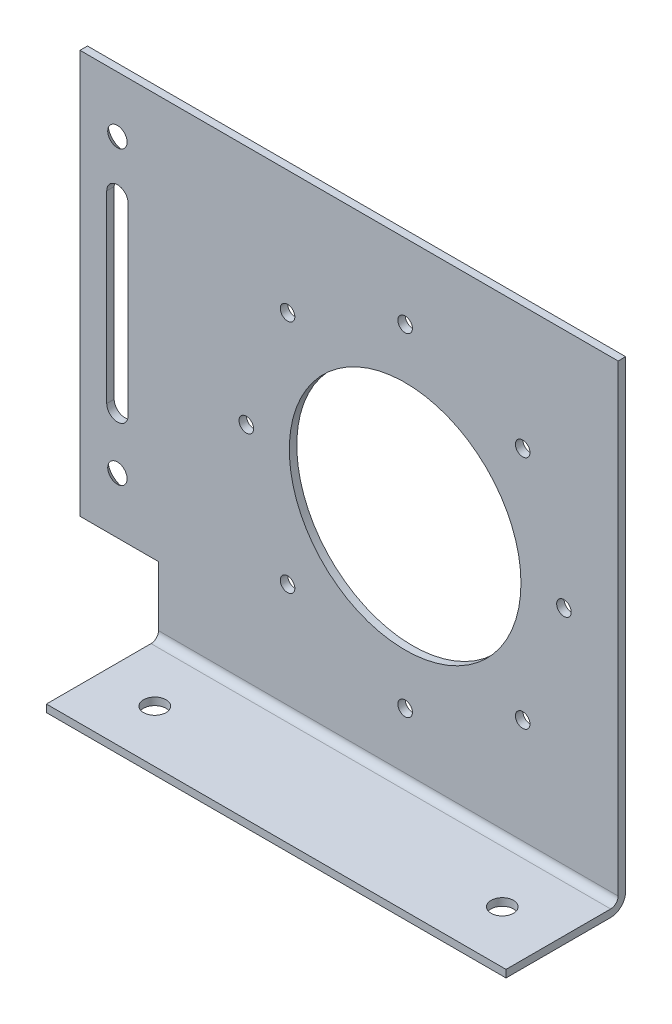
SolidWorks part; units mm, degrees
ref_plane "Ebene vorne" through (0, 0, 0) normal (0, 0, 1) x (1, 0, 0)
ref_plane "Ebene oben" through (0, 0, 0) normal (0, 1, 0) x (1, 0, 0)
ref_plane "Ebene rechts" through (0, 0, 0) normal (1, 0, 0) x (0, 0, -1)
sketch "Skizze1" plane through (0, 0, 0) normal (0, 0, 1) x (1, 0, 0)
  line L0 (-69.0234, -46.6458) -> (-48.0234, -46.6458)
  line L1 (74.9766, -66.6458) -> (-48.0234, -66.6458)
  line L2 (74.9766, -66.6458) -> (74.9766, 61.3542)
  line L3 (74.9766, 61.3542) -> (-69.0234, 61.3542)
  line L4 (-69.0234, -46.6458) -> (-69.0234, 61.3542)
  line L5 (74.9766, -66.6458) -> (-69.0234, 61.3542) construction
  line L6 (74.9766, 61.3542) -> (-48.0234, -39.2981) construction
  line L7 (-48.0234, -46.6458) -> (-48.0234, -66.6458)
  point P0 (0, 0)
  dimension "D1" = 128
  dimension "D2" = 144
  dimension "D3" = 21
  dimension "D4" = 20
extrude "Aufsatz-Linear austragen1" add sketch "Skizze1" along normal blind 2
sketch "Skizze2" plane through (0, 0, 0) normal (0, 0, -1) x (-1, 0, 0)
  line L1 (-74.9766, -66.6458) -> (48.0234, -66.6458)
  line L2 (-74.9766, -66.6458) -> (-74.9766, -64.6458)
  line L3 (-74.9766, -64.6458) -> (48.0234, -64.6458)
  line L5 (48.0234, -64.6458) -> (48.0234, -66.6458)
  line L6 (48.0234, -46.6458) -> (48.0234, -66.6458) construction
  dimension "D1" = 2
extrude "Aufsatz-Linear austragen2" add sketch "Skizze2" along normal blind 30
fillet "Verrundung1" radius 2 1 edges at (13.4766, -64.6458, 0)
fillet "Verrundung2" radius 4 1 edges at (13.4766, -66.6458, 2)
sketch "Skizze3" plane through (0, -66.6458, 0) normal (0, -1, 0) x (1, 0, 0)
  line L0 (-48.0234, -16) -> (74.9766, -16) construction
  line L1 (-48.0234, -2) -> (-48.0234, -30) construction
  line L2 (74.9766, -2) -> (74.9766, -30) construction
  circle A0 centre (-33.0234, -16) radius 3
  circle A1 centre (59.9766, -16) radius 3
  dimension "D1" = 15
  dimension "D3" = 6
  dimension "D2" = 15
extrude "Schnitt-Linear austragen1" cut sketch "Skizze3" against normal through all
hole_wizard "Formsenkung für M4 Senkschraube mit Innensechskant1" positions "Skizze6" profile "Skizze5" countersink size "M4" standard "DIN"
sketch "Skizze6" plane through (0, 0, 2) normal (0, 0, 1) x (1, 0, 0)
  line L0 (-59.0234, 61.3542) -> (-59.0234, -46.6458) construction
  line L1 (74.9766, 61.3542) -> (-69.0234, 61.3542) construction
  line L2 (-69.0234, -46.6458) -> (-48.0234, -46.6458) construction
  line L4 (-69.0234, 61.3542) -> (-69.0234, -46.6458) construction
  point P8 (-59.0234, 46.3542)
  point P10 (-59.0234, -31.6458)
  dimension "D1" = 15
  dimension "D2" = 15
  dimension "D3" = 10
sketch "Skizze5" plane through (-59.0234, -31.6458, 2) normal (1, 0, 0) x (0, -1, 0)
  line L0 (0, 0) -> (0, 13.2919)
  line L1 (0, 13.2919) -> (2.25, 11.94)
  line L2 (2.25, 11.94) -> (2.25, 2.34)
  line L3 (2.25, 2.34) -> (4.59, 0)
  line L5 (4.59, 0) -> (0, 0)
  line L6 (-2.25, 2.34) -> (-4.59, 0) construction
  line L10 (0, 13.2919) -> (-2.25, 11.94) construction
  line L11 (0, -6.35) -> (0, 107.95) construction
  dimension "Bohrerdurchmesser" = 4.5
  dimension "Bohrungstiefe" = 11.94
  dimension "Senkdurchmesser (Oben)" = 9.18
  dimension "Senkwinkel (Oben)" = 90
  dimension "Spitzenwinkel" = 118
sketch "Skizze7" plane through (0, 0, 2) normal (0, 0, 1) x (1, 0, 0)
  line L0 (-59.0234, 46.3542) -> (-59.0234, -31.6458) construction
  line L1 (-59.0234, -16.9352) -> (-59.0234, 32.3542) construction
  line L2 (-61.8817, -16.9352) -> (-61.8817, 32.3542)
  line L3 (-56.1652, -16.9352) -> (-56.1652, 32.3542)
  line L4 (74.9766, -62.6458) -> (74.9766, 61.3542) construction
  line L5 (74.9766, 61.3542) -> (-69.0234, 61.3542) construction
  circle A0 centre (17.9766, -3.1458) radius 44.5 construction
  circle A1 centre (17.9766, 41.3542) radius 1.95
  circle A2 centre (17.9766, -3.1458) radius 44.5 construction
  circle A3 centre (49.4428, 28.3204) radius 1.95
  circle A4 centre (17.9766, -3.1458) radius 44.5 construction
  circle A6 centre (17.9766, -3.1458) radius 44.5 construction
  circle A7 centre (49.4428, -34.6121) radius 1.95
  circle A8 centre (17.9766, -3.1458) radius 44.5 construction
  circle A9 centre (17.9766, -47.6458) radius 1.95
  circle A10 centre (17.9766, -3.1458) radius 44.5 construction
  circle A11 centre (-13.4897, -34.6121) radius 1.95
  circle A12 centre (17.9766, -3.1458) radius 44.5 construction
  circle A14 centre (17.9766, -3.1458) radius 44.5 construction
  circle A15 centre (-13.4897, 28.3204) radius 1.95
  circle A16 centre (17.9766, -3.1458) radius 31
  circle A17 centre (-26.5234, -3.1458) radius 1.95 [skipped]
  circle A18 centre (62.4766, -3.1458) radius 1.95 [skipped]
  circle A19 centre (17.9766, -3.1458) radius 42.5 construction
  circle A20 centre (-24.5234, -3.1458) radius 1.95
  circle A21 centre (60.4766, -3.1458) radius 1.95
  circle A22 centre (-59.0234, -31.6458) radius 2.59 construction
  circle A23 centre (-59.0234, 46.3542) radius 2.59 construction
  circle A24 centre (-59.0234, -31.6458) radius 2.59 construction
  circle A25 centre (-59.0234, 46.3542) radius 2.59 construction
  arc A26 (-61.8817, -16.9352) -> (-56.1652, -16.9352) centre (-59.0234, -16.9352) ccw
  arc A27 (-56.1652, 32.3542) -> (-61.8817, 32.3542) centre (-59.0234, 32.3542) ccw
  point P29 (17.9766, -3.1458)
  point P44 (-59.0234, 7.7095)
  dimension "D1" = 89
  dimension "D2" = 3.9
  dimension "D4" = 85
  dimension "D5" = 62
  dimension "D6" = 57
  dimension "D7" = 64.5
  dimension "D9" = 14
  dimension "D10" = 14.7106
  dimension "D3" = 8
extrude "Schnitt-Linear austragen2" cut sketch "Skizze7" against normal through all
mirror "Spiegeln2" about plane through (0, 0, 2) normal (0, 0, 1) of bodies 106
delete or keep bodies "Körper-Löschen/beibehalten 1" type delete bodies bodies 106
